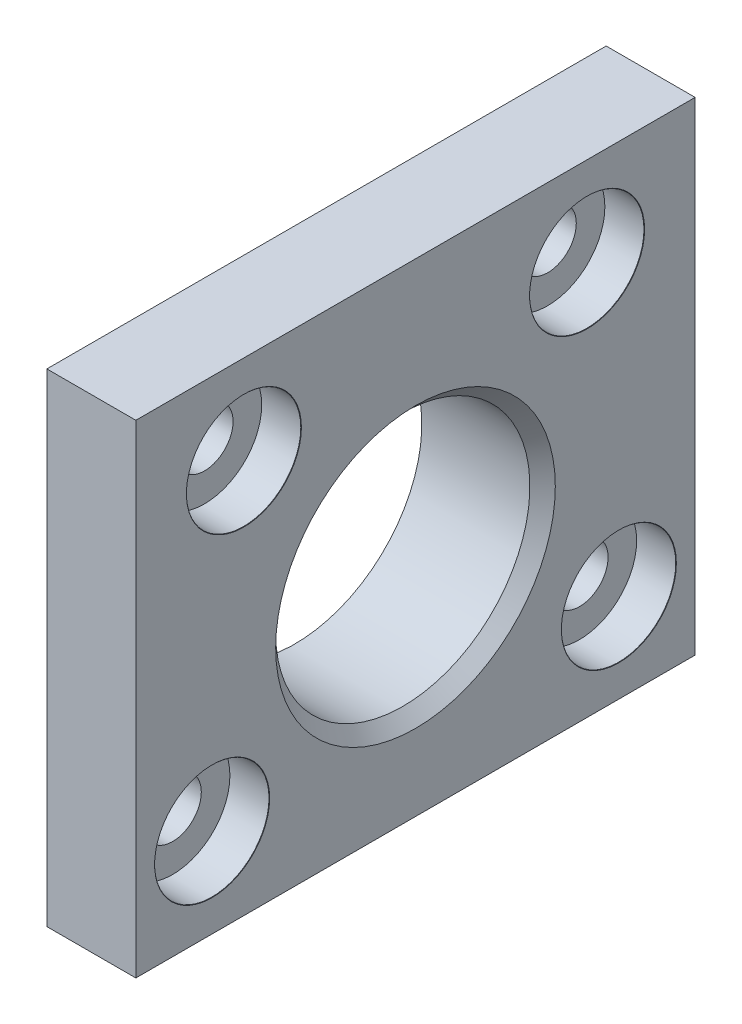
SolidWorks part; units mm, degrees
ref_plane "Plano frontal" through (0, 0, 0) normal (0, 0, 1) x (1, 0, 0)
ref_plane "Plano superior" through (0, 0, 0) normal (0, 1, 0) x (1, 0, 0)
ref_plane "Plano direito" through (0, 0, 0) normal (1, 0, 0) x (0, 0, -1)
sketch "Esboço1" plane through (0, 0, 0) normal (1, 0, 0) x (0, 0, -1)
  line L1 (44, 38) -> (0, 38)
  line L2 (44, 38) -> (44, 0)
  line L3 (44, 0) -> (0, 0)
  line L4 (0, 38) -> (0, 0)
  circle A0 centre (22, 17) radius 10
  dimension "D3" = 17
  dimension "D4" = 20
  dimension "D1" = 44
  dimension "D2" = 38
  dimension "D5" = 22
extrude "Ressalto-extrusão1" add sketch "Esboço1" against normal blind 7
sketch "Esboço2" plane through (-7, 0, 0) normal (-1, 0, 0) x (0, 0, 1)
  circle A0 centre (-22, 17) radius 10
  circle A1 centre (-22, 17) radius 15.4
  circle A2 centre (-22, 17) radius 10 construction
  dimension "D1" = 30.8
extrude "Ressalto-extrusão2" add sketch "Esboço2" along normal blind 2.5
chamfer "Chanfro1" distance 1 angle 45 1 edges at (0, 17, -32)
hole_wizard "Rebaixo para parafuso com cabeça panela de M41" positions "Esboço3" profile "Esboço4" counterbore size "M4" standard "ISO" end condition through all
sketch "Esboço3" plane through (0, 0, 0) normal (1, 0, 0) x (0, 0, -1)
  line L0 (0, 0) -> (44, 0) construction
  line L1 (44, 38) -> (0, 38) construction
  point P0 (8.5, 31)
  point P2 (35.5, 31)
  point P4 (38, 7)
  point P6 (6, 7)
  point P13 (22, 38)
  point P14 (0, 0)
  point P15 (22, 0)
  point P16 (0, 0)
  dimension "D1" = 27
  dimension "D2" = 32
  dimension "D3" = 7
  dimension "D4" = 13.5
  dimension "D5" = 7
  dimension "D6" = 16
sketch "Esboço4" plane through (0, 31, -8.5) normal (0, 1, 0) x (0, 0, -1)
  line L0 (0, 0) -> (0, 9.5)
  line L1 (0, 9.5) -> (2.25, 9.5)
  line L3 (2.25, 9.5) -> (2.25, 3.1)
  line L4 (4.5, 3.1) -> (2.25, 3.1)
  line L5 (4.5, 3.1) -> (4.5, 0.025)
  line L6 (4.5, 0.025) -> (4.525, 0)
  line L7 (4.525, 0) -> (0, 0)
  line L8 (-4.5, 0.025) -> (-4.525, 0) construction
  line L11 (0, -6.35) -> (0, 107.95) construction
  dimension "Thru Hole Dia." = 4.5
  dimension "Thru Hole Depth" = 9.5
  dimension "C'Bore Dia." = 9
  dimension "C'Bore Depth" = 3.1
  dimension "Near C'Sink Dia." = 9.05
  dimension "Near C'Sink Angle" = 90
